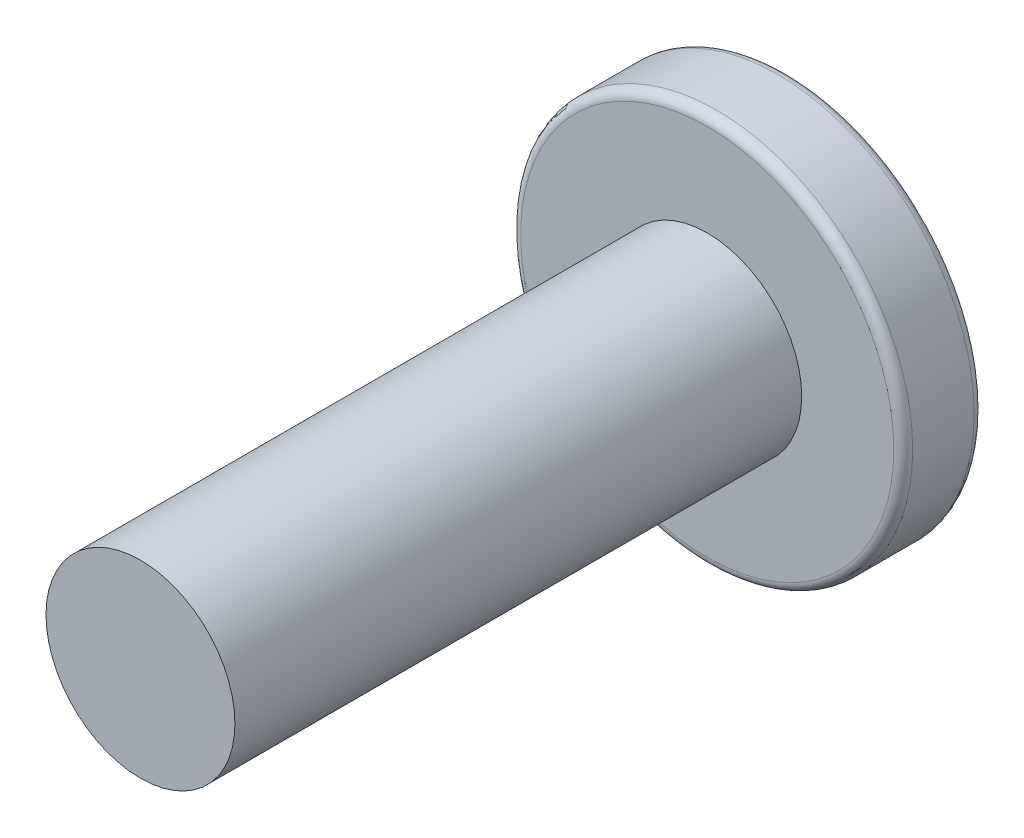
SolidWorks part; units mm, degrees
material "AISI 304"
ref_plane "前视基准面" through (0, 0, 0) normal (0, 0, 1) x (1, 0, 0)
ref_plane "上视基准面" through (0, 0, 0) normal (0, 1, 0) x (1, 0, 0)
ref_plane "右视基准面" through (0, 0, 0) normal (1, 0, 0) x (0, 0, -1)
other "Configuration Table"
sketch "草图1" plane through (0, 0, 0) normal (0, 0, 1) x (1, 0, 0)
  circle A0 centre (0, 0) radius 4.15
  dimension "D1" = 8.3
extrude "凸台-拉伸1" add sketch "草图1" along normal blind 1.7
sketch "草图2" plane through (0, 0, 1.7) normal (0, 0, 1) x (1, 0, 0)
  circle A1 centre (0, 0) radius 2
  dimension "D2" = 4
extrude "凸台-拉伸2" add sketch "草图2" along normal blind 12
fillet "圆角1" radius 0.2 2 edges at (4.15, 0, 0) (4.15, 0, 1.7)
sketch "草图3" plane through (0, 0, 0) normal (0, 0, -1) x (-1, 0, 0)
  line L0 (0, 0) -> (1.1547, 0) construction
  line L1 (1.1547, 0) -> (0.5774, 1)
  line L2 (0.5774, 1) -> (-0.5774, 1)
  line L3 (-0.5774, 1) -> (-1.1547, 0)
  line L4 (-1.1547, 0) -> (-0.5774, -1)
  line L5 (-0.5774, -1) -> (0.5774, -1)
  line L6 (0.5774, -1) -> (1.1547, 0)
  circle A0 centre (0, 0) radius 1 construction
  dimension "D1" = 2
extrude "切除-拉伸1" cut sketch "草图3" against normal blind 1.5
